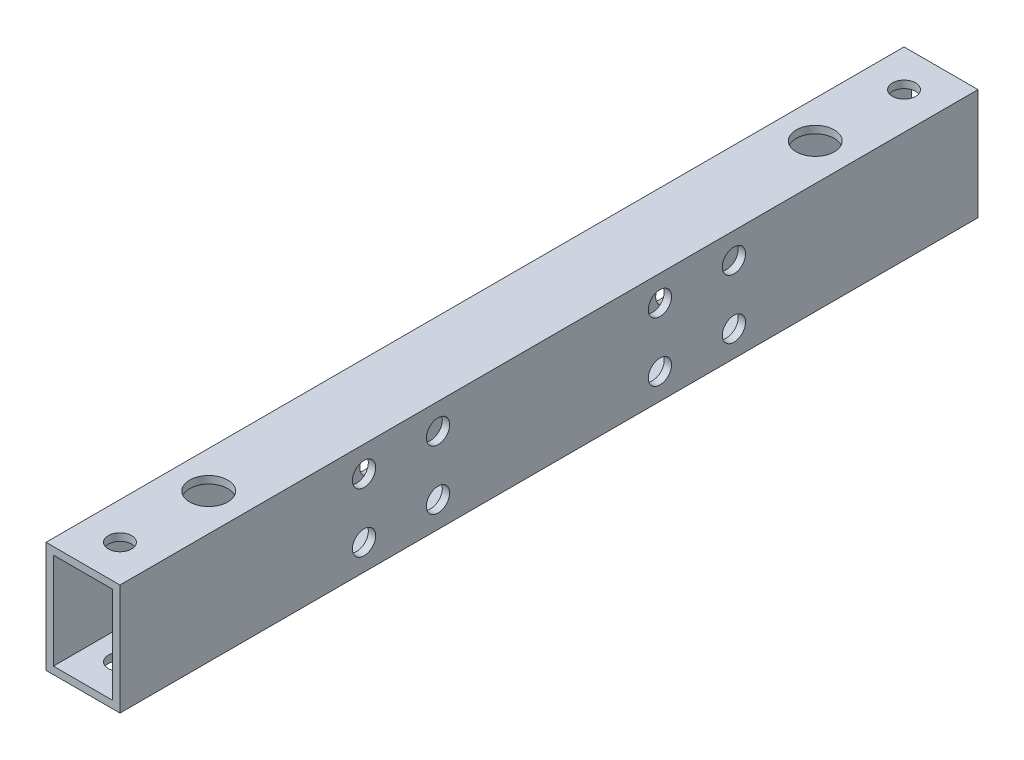
SolidWorks part; units mm, degrees
ref_plane "前视基准面" through (0, 0, 0) normal (0, 0, 1) x (1, 0, 0)
ref_plane "上视基准面" through (0, 0, 0) normal (0, 1, 0) x (1, 0, 0)
ref_plane "右视基准面" through (0, 0, 0) normal (1, 0, 0) x (0, 0, -1)
other "Configuration Table"
sketch "草图1" plane through (0, 0, 0) normal (0, 0, 1) x (1, 0, 0)
  line L1 (0, 0) -> (10, 0)
  line L2 (0, 0) -> (0, -15)
  line L3 (0, -15) -> (10, -15)
  line L4 (10, 0) -> (10, -15)
  dimension "D1" = 10
  dimension "D2" = 15
extrude "拉伸-薄壁1" add sketch "草图1" along normal blind 116 thin contours L1 L4 L3 L2
sketch "草图2" plane through (0, 0, 0) normal (0, 1, 0) x (1, 0, 0)
  line L0 (0, -58) -> (10, -58) construction
  line L1 (0, -116) -> (0, 0) construction
  line L2 (10, -116) -> (10, 0) construction
  line L3 (5, -58) -> (5, -17) construction
  circle A0 centre (5, -5) radius 1.575
  circle A1 centre (5, -17) radius 2.575
  circle A2 centre (5, -99) radius 2.575
  circle A3 centre (5, -111) radius 1.575
  point P10 (10, -27.9343)
  point P12 (10, -8.7064)
  point P13 (0, 0)
  point P14 (10, -3.7487)
  point P15 (10, -2.7504)
  dimension "D1" = 5.15
  dimension "D2" = 3.15
  dimension "D3" = 41
  dimension "D4" = 12
extrude "切除-拉伸1" cut sketch "草图2" against normal through all
sketch "草图3" plane through (0, 0, 0) normal (-1, 0, 0) x (0, 0, 1)
  line L0 (58, 0) -> (58, -15) construction
  line L1 (116, 0) -> (0, 0) construction
  line L2 (116, -15) -> (0, -15) construction
  line L3 (38, 0) -> (38, -15) construction
  line L4 (0, -7.5) -> (38, -7.5) construction
  line L5 (0, 0) -> (0, -15) construction
  line L6 (78, 0) -> (78, -15) construction
  circle A0 centre (33, -3.5) radius 1.575
  circle A1 centre (43, -3.5) radius 1.575
  circle A2 centre (43, -11.5) radius 1.575
  circle A3 centre (33, -11.5) radius 1.575
  circle A4 centre (83, -11.5) radius 1.575
  circle A5 centre (73, -11.5) radius 1.575
  circle A6 centre (73, -3.5) radius 1.575
  circle A7 centre (83, -3.5) radius 1.575
  dimension "D1" = 3.15
  dimension "D2" = 8
  dimension "D3" = 5
  dimension "D4" = 20
extrude "切除-拉伸2" cut sketch "草图3" against normal through all
